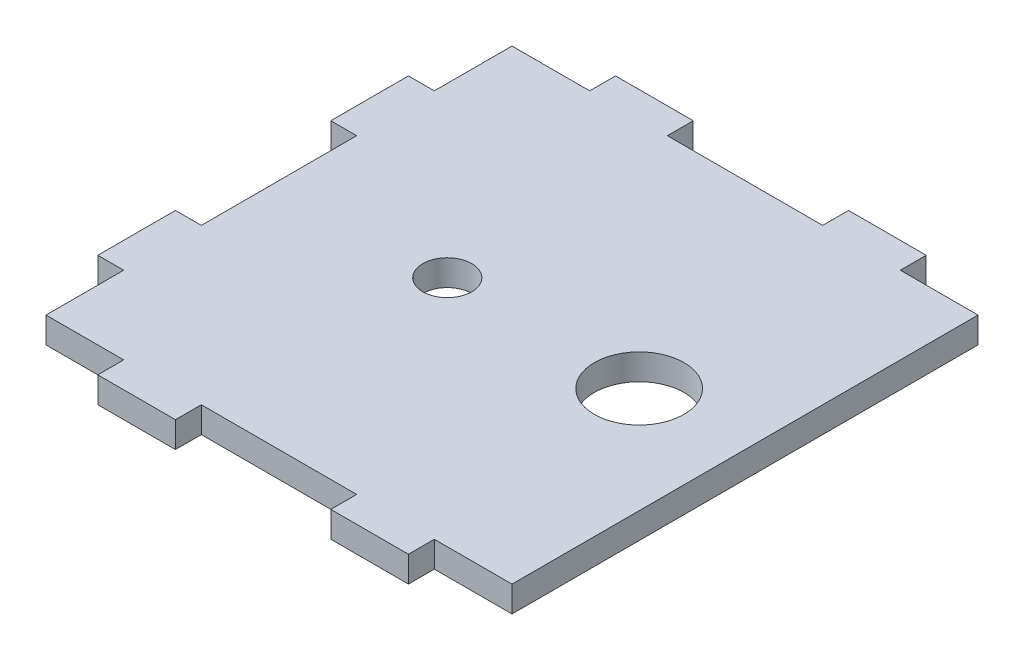
SolidWorks part; units mm, degrees
ref_plane "Front Plane" through (0, 0, 0) normal (0, 0, 1) x (1, 0, 0)
ref_plane "Top Plane" through (0, 0, 0) normal (0, 1, 0) x (1, 0, 0)
ref_plane "Right Plane" through (0, 0, 0) normal (1, 0, 0) x (0, 0, -1)
sketch "Sketch1" plane through (0, 0, 0) normal (0, 1, 0) x (1, 0, 0)
  line L0 (0, 57.15) -> (184.6638, 57.15) construction
  line L1 (0, 0) -> (19.05, 0)
  line L2 (0, 0) -> (0, 19.05)
  line L3 (0, 114.3) -> (19.05, 114.3)
  line L4 (114.3, 0) -> (114.3, 114.3)
  line L5 (38.1, 0) -> (76.2, 0)
  line L7 (95.25, 0) -> (95.25, -6.35)
  line L8 (95.25, -6.35) -> (76.2, -6.35)
  line L9 (76.2, 0) -> (76.2, -6.35)
  line L11 (19.05, 0) -> (19.05, -6.35)
  line L12 (19.05, -6.35) -> (38.1, -6.35)
  line L13 (38.1, 0) -> (38.1, -6.35)
  line L14 (95.25, 0) -> (114.3, 0)
  line L15 (38.1, 114.3) -> (38.1, 120.65)
  line L16 (19.05, 120.65) -> (38.1, 120.65)
  line L17 (19.05, 114.3) -> (19.05, 120.65)
  line L18 (76.2, 114.3) -> (76.2, 120.65)
  line L19 (95.25, 120.65) -> (76.2, 120.65)
  line L20 (95.25, 114.3) -> (95.25, 120.65)
  line L21 (38.1, 114.3) -> (76.2, 114.3)
  line L23 (95.25, 114.3) -> (114.3, 114.3)
  line L24 (-6.35, 19.05) -> (-6.35, 38.1)
  line L25 (0, 95.25) -> (-6.35, 95.25)
  line L27 (0, 76.2) -> (-6.35, 76.2)
  line L28 (-6.35, 95.25) -> (-6.35, 76.2)
  line L29 (0, 38.1) -> (-6.35, 38.1)
  line L31 (0, 19.05) -> (-6.35, 19.05)
  line L32 (0, 95.25) -> (0, 114.3)
  line L33 (0, 38.1) -> (0, 76.2)
  dimension "D1" = 114.3
  dimension "D2" = 114.3
  dimension "D3" = 19.05
  dimension "D4" = 19.05
  dimension "D5" = 19.05
  dimension "D6" = 19.05
  dimension "D7" = 6.35
  dimension "D8" = 6.35
  dimension "D9" = 19.05
  dimension "D10" = 19.05
extrude "Boss-Extrude1" add sketch "Sketch1" against normal blind 6.35
sketch "Sketch5" plane through (0, 0, 0) normal (0, 1, 0) x (1, 0, 0)
  line L0 (114.3, 57.15) -> (5.9998, 57.15) construction
  line L1 (114.3, 0) -> (114.3, 114.3) construction
  line L2 (3.175, 78.7113) -> (3.175, 29.9896) construction
  line L3 (0, 76.2) -> (0, 38.1) construction
  circle A0 centre (88.3412, 57.15) radius 10.16 construction
  circle A1 centre (41.275, 57.15) radius 38.1 construction
  dimension "D1" = 20.32
  dimension "D2" = 76.2
  dimension "D4" = 3.175
  dimension "D3" = 47.0662
sketch "Sketch2" plane through (0, 0, 0) normal (0, 1, 0) x (1, 0, 0)
  circle A2 centre (88.3412, 57.15) radius 11
  circle A3 centre (88.3412, 57.15) radius 10.16 construction
  circle A4 centre (88.3412, 57.15) radius 10.16 construction
  circle A5 centre (41.275, 57.15) radius 38.1 construction
  circle A6 centre (41.275, 57.15) radius 38.1 construction
  circle A7 centre (41.275, 57.15) radius 6
  dimension "D1" = 12
  dimension "D2" = 22
extrude "Cut-Extrude1" cut sketch "Sketch2" against normal through all
sketch "Sketch3" [suppressed] plane through (0, 0, 0) normal (0, 1, 0) x (1, 0, 0)
  line L0 (90.7, 57.15) -> (-12.2602, 122.2732) construction
  line L1 (87.3056, 51.7834) -> (-15.6546, 116.9066)
  line L2 (94.0944, 62.5166) -> (-8.8658, 127.6398)
  line L3 (90.7, 57.15) -> (22.3264, 57.15) construction
  line L4 (90.7, 57.15) -> (-12.2602, -7.9732) construction
  line L5 (87.3056, 62.5166) -> (-15.6546, -2.6066)
  line L6 (94.0944, 51.7834) -> (-8.8658, -13.3398)
  line L35 (90.7, 57.15) -> (-12.2602, 57.15) construction
  line L36 (90.7, 50.8) -> (-12.2602, 50.8)
  line L37 (90.7, 63.5) -> (-12.2602, 63.5)
  line L63 (12.7, 12.7) -> (101.6, 12.7)
  line L64 (101.6, 12.7) -> (101.6, 101.6)
  line L65 (101.6, 101.6) -> (12.7, 101.6)
  line L66 (12.7, 101.6) -> (12.7, 12.7)
  line L67 (12.7, 12.7) -> (101.6, 12.7)
  line L68 (101.6, 12.7) -> (101.6, 101.6)
  line L69 (101.6, 101.6) -> (12.7, 101.6)
  line L70 (12.7, 101.6) -> (12.7, 12.7)
  arc A0 (87.3056, 51.7834) -> (94.0944, 62.5166) centre (90.7, 57.15) ccw
  arc A1 (-8.8658, 127.6398) -> (-15.6546, 116.9066) centre (-12.2602, 122.2732) ccw
  arc A3 (87.3056, 62.5166) -> (94.0944, 51.7834) centre (90.7, 57.15) cw
  circle A4 centre (90.7, 57.15) radius 29.95
  circle A5 centre (90.7, 57.15) radius 29.95
  arc A6 (-8.8658, -13.3398) -> (-15.6546, -2.6066) centre (-12.2602, -7.9732) cw
  arc A7 (90.7, 50.8) -> (90.7, 63.5) centre (90.7, 57.15) ccw
  arc A8 (-12.2602, 63.5) -> (-12.2602, 50.8) centre (-12.2602, 57.15) ccw
  point P2 (39.2199, 89.7116)
  point P8 (39.2199, 24.5884)
  point P19 (39.2199, 57.15)
  dimension "D2" = 6.35
  dimension "D1" = 12.7
  dimension "D3" = 12.7
extrude "Cut-Extrude2" [suppressed] cut sketch "Sketch3" against normal through all contours A5 L68 L69 L2 | A5 L1 L70 L37 | A5 L36 L70 L5 | A5 L6 L67 L68
fillet "Fillet1" [suppressed] radius 2.54
sketch "Sketch4" [suppressed] plane through (0, 0, 0) normal (0, 1, 0) x (1, 0, 0)
  line L0 (0, 171.45) -> (6.35, 171.45)
  line L1 (6.35, 171.45) -> (95.25, 120.65)
  line L2 (95.25, 120.65) -> (76.2, 120.65) construction
  line L3 (0, 120.65) -> (0, 136.525)
  line L4 (0, 114.3) -> (0, 95.25) construction
  line L9 (19.05, 114.3) -> (0, 114.3) construction
  line L10 (0, 155.575) -> (0, 171.45)
  line L11 (95.25, 114.3) -> (95.25, 120.65) construction
  line L12 (0, 120.65) -> (19.05, 120.65)
  line L13 (-6.35, 155.575) -> (-6.35, 136.525)
  line L14 (-6.35, 136.525) -> (0, 136.525)
  line L16 (0, 155.575) -> (-6.35, 155.575)
  line L17 (19.05, 120.65) -> (95.25, 120.65)
  dimension "D1" = 6.35
  dimension "D2" = 22.225
  dimension "D3" = 6.35
  dimension "D4" = 19.05
  dimension "D5" = 15.875
extrude "Boss-Extrude2" [suppressed] add sketch "Sketch4" against normal blind 6.35
